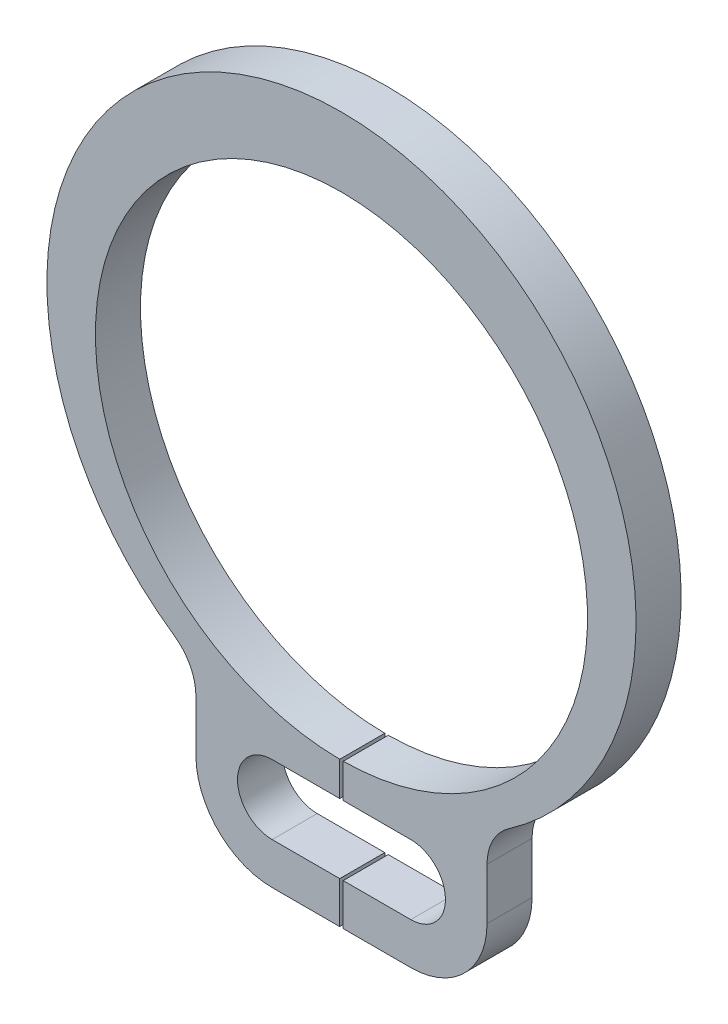
SolidWorks part; units mm, degrees
material "不锈钢 (铁素体)"
ref_plane "前视基准面" through (0, 0, 0) normal (0, 0, 1) x (1, 0, 0)
ref_plane "上视基准面" through (0, 0, 0) normal (0, 1, 0) x (1, 0, 0)
ref_plane "右视基准面" through (0, 0, 0) normal (1, 0, 0) x (0, 0, -1)
sketch "草图1" plane through (0, 0, 0) normal (0, 0, 1) x (1, 0, 0)
  line L0 (0, 1.0126) -> (0, -2.147) construction
  line L1 (-1, -5.6412) -> (1, -5.6412)
  line L2 (-2.1, -4.5412) -> (-2.1, -3.3949)
  line L3 (2.1, -4.5412) -> (2.1, -3.3949)
  circle A0 centre (0, 0) radius 3.55
  arc A1 (2.1, -3.3949) -> (-2.1, -3.3949) centre (0, 0.3) ccw
  circle A2 centre (-1, -4.5412) radius 0.5
  circle A4 centre (1, -4.5412) radius 0.5
  arc A5 (2.1, -4.5412) -> (1, -5.6412) centre (1, -4.5412) cw
  arc A6 (-2.1, -4.5412) -> (-1, -5.6412) centre (-1, -4.5412) ccw
  dimension "d3" = 7.1
  dimension "d0" = 1
  dimension "a" = 2.2
  dimension "b" = 1
  dimension "O1O2" = 0.3
  dimension "O3O4" = 2
extrude "凸台-拉伸1" add sketch "草图1" along normal blind 0.65
sketch "草图2" plane through (0, 0, 0.65) normal (0, 0, 1) x (1, 0, 0)
  line L0 (-1, -5.6412) -> (1, -5.6412) construction
  line L1 (-0.025, -5.6412) -> (0.025, -5.6412)
  line L2 (-0.025, -5.6412) -> (-0.025, 0)
  line L3 (-0.025, 0) -> (0.025, 0)
  line L4 (0.025, -5.6412) -> (0.025, 0)
  dimension "k" = 0.05
extrude "切除-拉伸1" cut sketch "草图2" against normal through all
fillet "圆角1" radius 0.7333 2 edges at (2.1, -3.3949, 0.325) (-2.1, -3.3949, 0.325)
sketch "草图3" plane through (0, 0, 0.65) normal (0, 0, 1) x (1, 0, 0)
  line L0 (-1, -4.5412) -> (1, -4.5412) construction
  line L1 (-1, -4.0412) -> (1, -4.0412)
  line L2 (-1, -5.0412) -> (1, -5.0412)
  arc A0 (-1, -4.0412) -> (-1, -5.0412) centre (-1, -4.5412) ccw
  arc A1 (1, -5.0412) -> (1, -4.0412) centre (1, -4.5412) ccw
  circle A2 centre (1, -4.5412) radius 0.5 construction
  point P4 (0, -4.5412)
extrude "切除-拉伸2" cut sketch "草图3" against normal through all
equation "\"D1@圆角1\" = \"a@草图1\" / 3"
